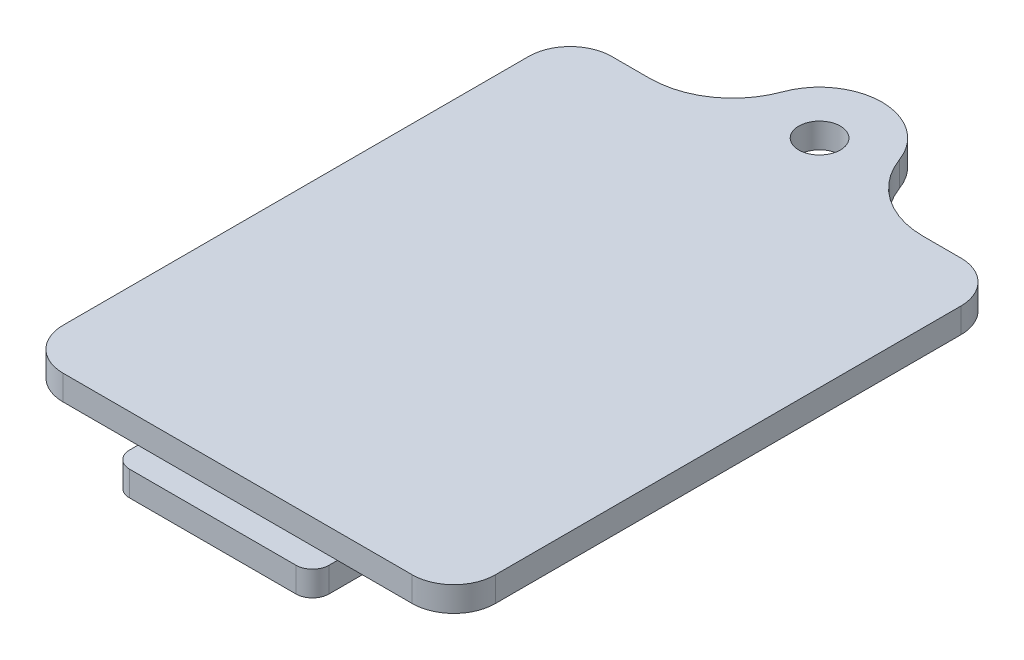
SolidWorks part; units mm, degrees
material "ABS PC"
ref_plane "Front Plane" through (0, 0, 0) normal (0, 0, 1) x (1, 0, 0)
ref_plane "Top Plane" through (0, 0, 0) normal (0, 1, 0) x (1, 0, 0)
ref_plane "Right Plane" through (0, 0, 0) normal (1, 0, 0) x (0, 0, -1)
sketch "Sketch1" plane through (0, 0, 0) normal (0, 1, 0) x (1, 0, 0)
  line L1 (-21, 66) -> (-16.4393, 66)
  line L2 (-26, 61) -> (-26, 5)
  line L3 (-21, 0) -> (21, 0)
  line L4 (26, 61) -> (26, 5)
  line L9 (16.4393, 66) -> (21, 66)
  line L16 (0, 33) -> (-26, 33) construction
  line L17 (26, 33) -> (0, 33) construction
  arc A0 (-26, 5) -> (-21, 0) centre (-21, 5) ccw
  arc A1 (26, 5) -> (21, 0) centre (21, 5) cw
  arc A2 (26, 61) -> (21, 66) centre (21, 61) ccw
  arc A3 (-26, 61) -> (-21, 66) centre (-21, 61) cw
  circle A4 centre (0, 70) radius 2.5
  arc A5 (7.0454, 72.5714) -> (-7.0454, 72.5714) centre (0, 70) ccw
  arc A6 (-16.4393, 66) -> (-7.0454, 72.5714) centre (-16.4393, 76) ccw
  arc A7 (16.4393, 66) -> (7.0454, 72.5714) centre (16.4393, 76) cw
  point P39 (6.3443, 66)
  dimension "D2" = 5
  dimension "D8" = 5
  dimension "D9" = 10
  dimension "D10" = 10
  dimension "D5" = 7.5
  dimension "D3" = 52
  dimension "D4" = 66
  dimension "D13" = 70
extrude "Boss-Extrude1" add sketch "Sketch1" along normal blind 3
sketch "Sketch2" plane through (0, 0, 0) normal (0, -1, 0) x (1, 0, 0)
  line L0 (0, 0) -> (0, -9) construction
  line L1 (-10, -9) -> (10, -9)
  line L2 (-12, -7) -> (-12, 1)
  line L3 (-10, 3) -> (10, 3)
  line L4 (12, -7) -> (12, 1)
  line L5 (-21, 0) -> (21, 0) construction
  arc A0 (12, 1) -> (10, 3) centre (10, 1) ccw
  arc A1 (-10, 3) -> (-12, 1) centre (-10, 1) ccw
  arc A2 (12, -7) -> (10, -9) centre (10, -7) cw
  arc A3 (-10, -9) -> (-12, -7) centre (-10, -7) cw
  point P11 (12, 3)
  point P16 (12, -9)
  dimension "D4" = 2
  dimension "D5" = 2
  dimension "D1" = 3
  dimension "D2" = 24
  dimension "D3" = 12
extrude "Boss-Extrude2" add sketch "Sketch2" along normal blind 3
